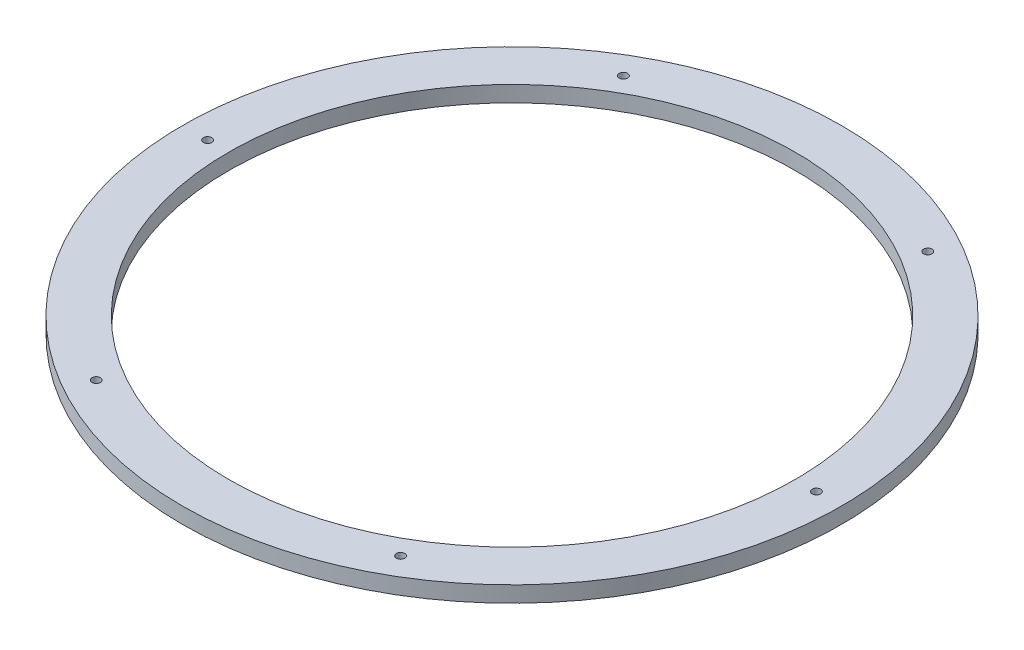
SolidWorks part; units mm, degrees
material "Pine"
ref_plane "Front Plane" through (0, 0, 0) normal (0, 0, 1) x (1, 0, 0)
ref_plane "Top Plane" through (0, 0, 0) normal (0, 1, 0) x (1, 0, 0)
ref_plane "Right Plane" through (0, 0, 0) normal (1, 0, 0) x (0, 0, -1)
sketch "Sketch1" plane through (0, 0, 0) normal (0, 1, 0) x (1, 0, 0)
  circle A0 centre (0, 0) radius 392.5
  circle A1 centre (0, 0) radius 337.5
  dimension "D1" = 785
  dimension "D2" = 675
extrude "Boss-Extrude1" add sketch "Sketch1" along normal mid plane 19
sketch "Sketch2" plane through (0, 9.5, 0) normal (0, 1, 0) x (1, 0, 0)
  line L0 (0, -1000) -> (0, 49000) construction
  line L1 (-1000, 0) -> (49000, 0) construction
  line L2 (-500, -866.0254) -> (24500, 42435.2448) construction
  line L3 (-498.7513, 863.8626) -> (24438.8143, -42329.268) construction
  circle A1 centre (181.25, 313.9342) radius 5
  circle A6 centre (0, 0) radius 362.5 construction
  circle A7 centre (362.5, 0) radius 5
  circle A8 centre (181.25, -313.9342) radius 5
  circle A9 centre (-181.25, -313.9342) radius 5
  circle A10 centre (-362.5, 0) radius 5
  circle A11 centre (-181.25, 313.9342) radius 5
  point P26 (0, 0)
  dimension "D1" = 6
  dimension "D2" = 10
  dimension "D3" = 725
  dimension "D7" = 30
  dimension "D8" = 30
extrude "Cut-Extrude1" cut sketch "Sketch2" against normal through all
